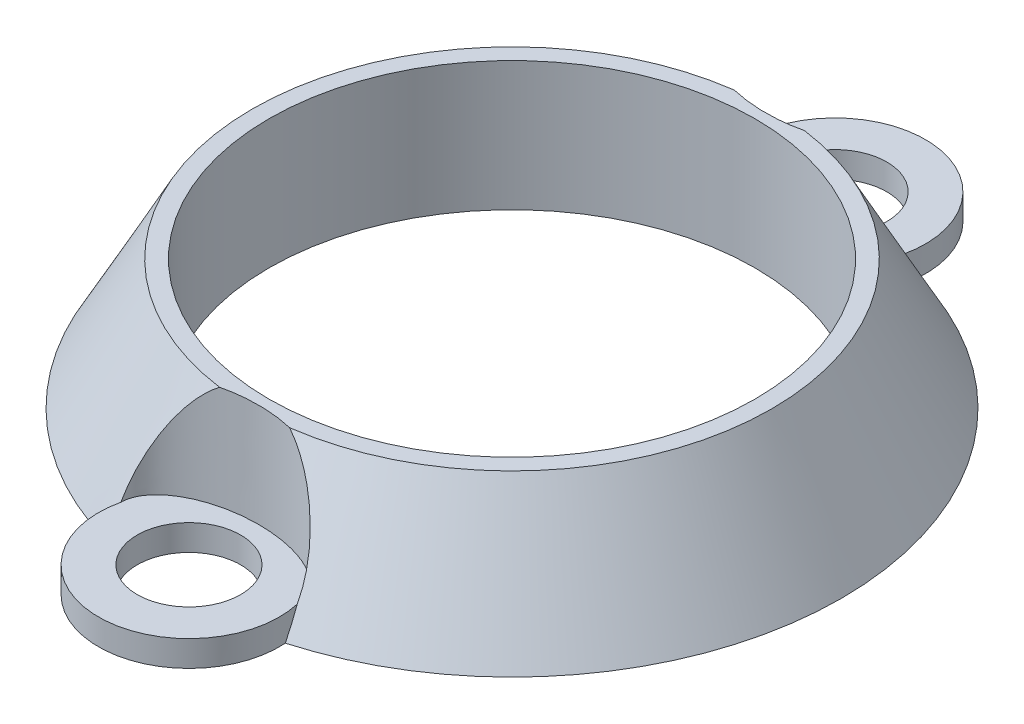
SolidWorks part; units mm, degrees
ref_plane "Plan de face" through (0, 0, 0) normal (0, 0, 1) x (1, 0, 0)
ref_plane "Plan de dessus" through (0, 0, 0) normal (0, 1, 0) x (1, 0, 0)
ref_plane "Plan de droite" through (0, 0, 0) normal (1, 0, 0) x (0, 0, -1)
sketch "Esquisse1" plane through (0, 0, 0) normal (0, 1, 0) x (1, 0, 0)
  arc A0 (-4.625, -8.0107) -> (4.625, -8.0107) centre (0, 0) ccw
  arc A3 (4.625, 8.0107) -> (-4.625, 8.0107) centre (0, 0) ccw
  arc A4 (-4.625, -8.0107) -> (-4.625, 8.0107) centre (0, 0) cw
  arc A5 (4.625, -8.0107) -> (4.625, 8.0107) centre (0, 0) ccw
  dimension "D1" = 18.5
extrude "Boss.-Extru.1" add sketch "Esquisse1" along normal blind 5 contours A0 A5 A3 A4
ref_axis "Axe1" through (0, 6.9782, 0) along (0, -1, 0)
sketch "Esquisse8" plane through (0, 0, 0) normal (0, 0, 1) x (1, 0, 0)
  line L1 (12.75, 0) -> (9.25, 0)
  line L2 (9.25, 0) -> (9.25, 5) construction
  line L3 (9.25, 0) -> (9.25, 5)
  line L4 (9.25, 5) -> (10.05, 5)
  line L5 (10.05, 5) -> (12.75, 0)
  dimension "D1" = 0.8
  dimension "D2" = 3.5
revolve "Révolution1" add sketch "Esquisse8" angle 360 about axis through (0, 6.9782, 0) along (0, -1, 0)
sketch "Esquisse12" plane through (0, 0, 0) normal (0, -1, 0) x (1, 0, 0)
  line L0 (0, -12.5) -> (0, 12.5) construction
  circle A0 centre (0, 12.5) radius 3.5
  circle A1 centre (0, -12.5) radius 3.5
  dimension "D2" = 7
  dimension "D1" = 25
extrude "Boss.-Extru.2" add sketch "Esquisse12" against normal blind 1
sketch "Esquisse10" plane through (0, 5, 0) normal (0, 1, 0) x (1, 0, 0)
  line L0 (-2.75, 0) -> (2.75, 0) construction
  circle A0 centre (0, 0) radius 10.05 construction
  ellipse E0 centre (0, 11.7234) end of major axis (3.4127, 11.7234) minor radius 1.9234
  ellipse E1 centre (0, -11.7234) end of major axis (3.4127, -11.7234) minor radius 1.9234
  dimension "D1" = 9.8
extrude "Enlèv. mat.-Extru.5" cut sketch "Esquisse10" against normal up to surface (4 mm away) up to face at (0, 1, -14.105)
sketch "Esquisse13" plane through (0, 1, 0) normal (0, 1, 0) x (1, 0, 0)
  circle A0 centre (0, 12.5) radius 2
  circle A1 centre (0, -12.5) radius 2
  arc A2 (-3.4127, -11.7234) -> (3.4127, -11.7234) centre (0, -12.5) ccw construction
  arc A3 (3.4127, 11.7234) -> (-3.4127, 11.7234) centre (0, 12.5) ccw construction
  dimension "D1" = 4
extrude "Enlèv. mat.-Extru.7" cut sketch "Esquisse13" against normal through all
sketch "Esquisse11" plane through (0, 5, 0) normal (0, 1, 0) x (1, 0, 0)
  circle A0 centre (0, 0) radius 9.4
  dimension "D1" = 18.8
extrude "Enlèv. mat.-Extru.6" cut sketch "Esquisse11" against normal through all
